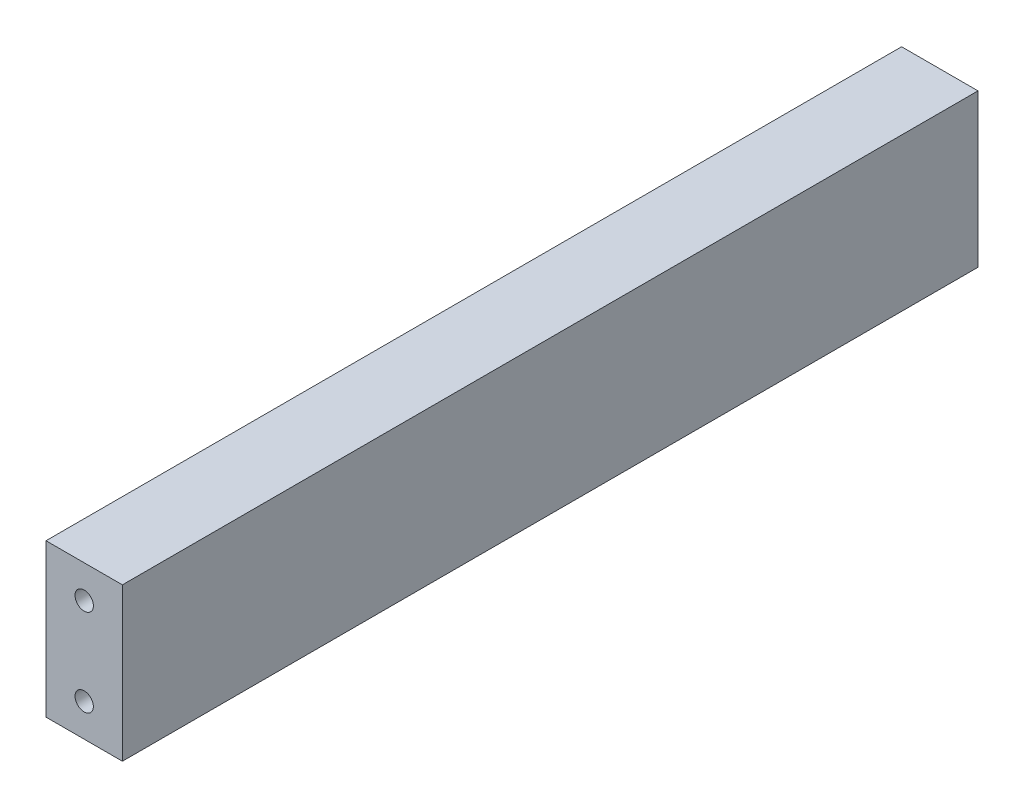
SolidWorks part; units mm, degrees
ref_plane "Ön Düzlem" through (0, 0, 0) normal (0, 0, 1) x (1, 0, 0)
ref_plane "Üst Düzlem" through (0, 0, 0) normal (0, 1, 0) x (1, 0, 0)
ref_plane "Sağ Düzlem" through (0, 0, 0) normal (1, 0, 0) x (0, 0, -1)
sketch "Çizim1" plane through (0, 0, 0) normal (0, 0, 1) x (1, 0, 0)
  line L1 (-8.75, -17.5) -> (8.75, -17.5)
  line L2 (-8.75, -17.5) -> (-8.75, 17.5)
  line L3 (-8.75, 17.5) -> (8.75, 17.5)
  line L4 (8.75, -17.5) -> (8.75, 17.5)
  line L5 (-8.75, -17.5) -> (8.75, 17.5) construction
  line L6 (-8.75, 17.5) -> (8.75, -17.5) construction
  point P0 (0, 0)
  dimension "D1" = 17.5
  dimension "D2" = 35
extrude "Yükseklik-Ekstrüzyon1" add sketch "Çizim1" along normal mid plane 196
sketch "Çizim2" plane through (0, 0, 98) normal (0, 0, 1) x (1, 0, 0)
  line L0 (0, -10) -> (0, 10) construction
  point P4 (0, 0)
  dimension "D1" = 20
hole_wizard "M5 Dişli Delik1" positions "3B Çizim1" profile "Çizim3" tap size "M5" standard "ISO"
sketch3d "3B Çizim1"
  point P0 (0, 10, 98)
  point P3 (0, -10, 98)
cosmetic thread "Delik Dişi1" parameters "D2"=5
cosmetic thread "Delik Dişi2" parameters "D2"=5
sketch "Çizim3" plane through (0, 10, 98) normal (1, 0, 0) x (0, -1, 0)
  line L0 (0, 0) -> (0, 201.2618)
  line L1 (0, 201.2618) -> (2.1, 200)
  line L2 (2.1, 200) -> (2.1, 0)
  line L5 (2.1, 0) -> (0, 0)
  line L10 (0, 201.2618) -> (-2.1, 200) construction
  line L11 (0, -6.35) -> (0, 107.95) construction
  dimension "Tap Drill Dia." = 4.2
  dimension "Tap Drill Depth" = 200
  dimension "Drill Angle" = 118
mirror "Aynalama1" about plane through (0, 0, 0) normal (0, 0, 1) of "M5 Dişli Delik1"
